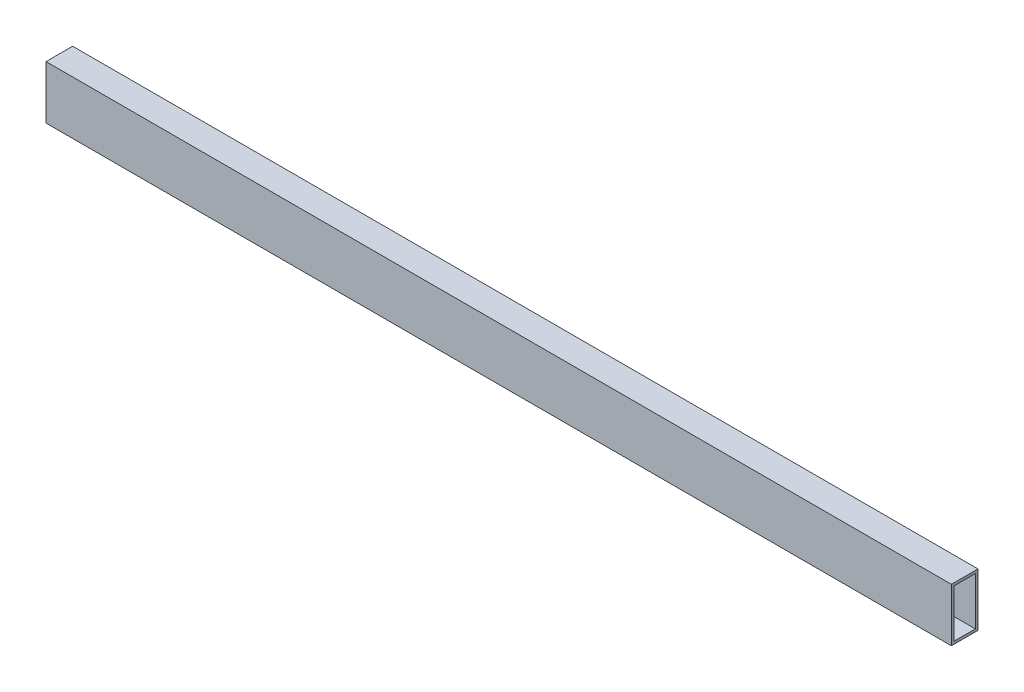
SolidWorks part; units mm, degrees
material "AISI 1015 Steel, Cold Drawn (SS)"
ref_plane "Front Plane" through (0, 0, 0) normal (0, 0, 1) x (1, 0, 0)
ref_plane "Top Plane" through (0, 0, 0) normal (0, 1, 0) x (1, 0, 0)
ref_plane "Right Plane" through (0, 0, 0) normal (1, 0, 0) x (0, 0, -1)
sketch "Sketch1" plane through (0, 0, 0) normal (1, 0, 0) x (0, 0, -1)
  line L0 (45, 5) -> (45, 95)
  line L1 (0, 0) -> (50, 0)
  line L2 (0, 0) -> (0, 100)
  line L3 (0, 100) -> (50, 100)
  line L4 (50, 0) -> (50, 100)
  line L5 (5, 95) -> (45, 95)
  line L6 (5, 5) -> (5, 95)
  line L7 (5, 5) -> (45, 5)
  dimension "D1" = 100
  dimension "D2" = 50
  dimension "D3" = 5
extrude "Boss-Extrude1" add sketch "Sketch1" along normal blind 1700
